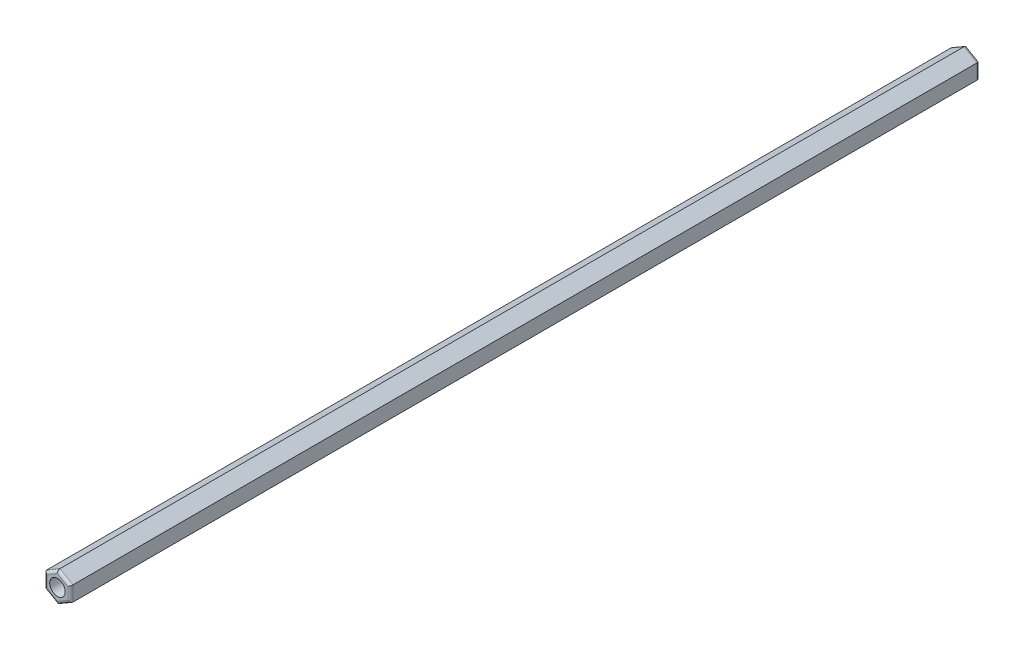
SolidWorks part; units mm, degrees
material "Inox rev"
ref_plane "Plano frontal" through (0, 0, 0) normal (0, 0, 1) x (1, 0, 0)
ref_plane "Plano superior" through (0, 0, 0) normal (0, 1, 0) x (1, 0, 0)
ref_plane "Plano direito" through (0, 0, 0) normal (1, 0, 0) x (0, 0, -1)
ref_plane "Plano1" through (0, 0, 0) normal (0, 0, -1) x (-1, 0, 0)
sketch "Esboço1" plane through (0, 0, 0) normal (0, 0, -1) x (-1, 0, 0)
  line L0 (67.5021, -1.4434) -> (70.0021, -2.8868)
  line L1 (70.0021, -2.8868) -> (72.5021, -1.4434)
  line L2 (72.5021, -1.4434) -> (72.5021, 1.4434)
  line L3 (72.5021, 1.4434) -> (70.0021, 2.8868)
  line L4 (70.0021, 2.8868) -> (67.5021, 1.4434)
  line L5 (67.5021, 1.4434) -> (67.5021, -1.4434)
extrude "Ressalto-extrusão1" add sketch "Esboço1" against normal blind 175
fillet "Filete1" radius 0.5 12 edges at (-71.2521, 2.1651, 0) (-72.5021, 0, 0) (-68.7521, 2.1651, 0) (-71.2521, -2.1651, 0) (-67.5021, 0, 0) (-68.7521, -2.1651, 0) (-71.2521, 2.1651, 175) (-72.5021, 0, 175) (-68.7521, 2.1651, 175) (-71.2521, -2.1651, 175) (-67.5021, 0, 175) (-68.7521, -2.1651, 175)
sketch "Esboço2" plane through (0, 0, 175) normal (0, 0, 1) x (1, 0, 0)
  circle A0 centre (-70.0021, 0) radius 1.5
  dimension "D1" = 3
extrude "Corte-extrusão1" cut sketch "Esboço2" against normal through all
